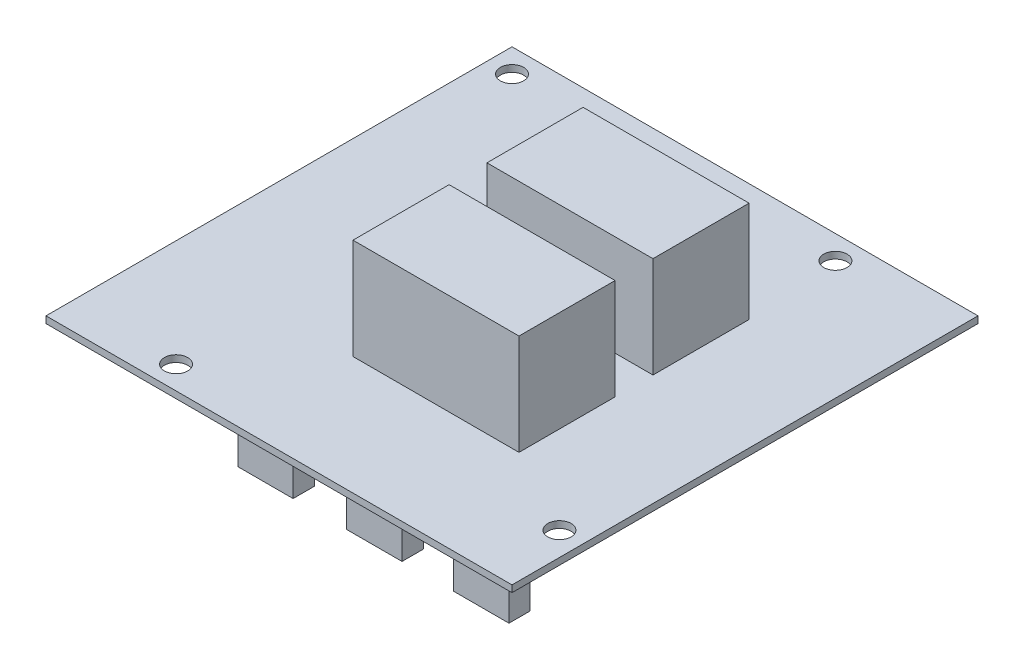
SolidWorks part; units mm, degrees
ref_plane "Front Plane" through (0, 0, 0) normal (0, 0, 1) x (1, 0, 0)
ref_plane "Top Plane" through (0, 0, 0) normal (0, 1, 0) x (1, 0, 0)
ref_plane "Right Plane" through (0, 0, 0) normal (1, 0, 0) x (0, 0, -1)
sketch "Esquisse1" plane through (0, 0, 0) normal (0, 1, 0) x (1, 0, 0)
  line L1 (-40, -40) -> (40, -40)
  line L2 (-40, -40) -> (-40, 40)
  line L3 (-40, 40) -> (40, 40)
  line L4 (40, -40) -> (40, 40)
  circle A0 centre (-35.94, 35.94) radius 2
  circle A1 centre (19.58, 35.94) radius 2
  circle A2 centre (35.94, -27.79) radius 2
  circle A3 centre (-21.64, -36.03) radius 2
  point P0 (0, 0)
  point P6 (0, 40)
  point P7 (40, 0)
  point P16 (0, 0)
  point P18 (29.6759, 35.463)
  dimension "D11" = 4
  dimension "D1" = 80
  dimension "D2" = 80
  dimension "D3" = 4.06
  dimension "D4" = 4.06
  dimension "D5" = 4.06
  dimension "D6" = 20.42
  dimension "D7" = 4.06
  dimension "D8" = 12.21
  dimension "D9" = 3.97
  dimension "D10" = 18.36
extrude "Boss.-Extru.1" add sketch "Esquisse1" along normal blind 1.16
sketch "Esquisse2" plane through (0, 1.16, 0) normal (0, 1, 0) x (1, 0, 0)
  line L0 (40, -40) -> (40, 40) construction
  line L1 (-7.6, 19.8) -> (20.9, 19.8)
  line L2 (-7.6, 19.8) -> (-7.6, 3.3)
  line L3 (-7.6, 3.3) -> (20.9, 3.3)
  line L4 (20.9, 19.8) -> (20.9, 3.3)
  line L5 (-7.6, -3.2) -> (20.9, -3.2)
  line L6 (-7.6, -3.2) -> (-7.6, -19.7)
  line L7 (-7.6, -19.7) -> (20.9, -19.7)
  line L8 (20.9, -3.2) -> (20.9, -19.7)
  line L9 (-40, -40) -> (40, -40) construction
  dimension "D1" = 6.5
  dimension "D2" = 28.5
  dimension "D3" = 19.1
  dimension "D4" = 20.3
  dimension "D5" = 16.5
extrude "Boss.-Extru.2" add sketch "Esquisse2" along normal blind 17.3
sketch "Esquisse3" plane through (0, 0, 0) normal (0, -1, 0) x (1, 0, 0)
  line L0 (-40, 40) -> (40, 40) construction
  line L1 (38.28, 35.15) -> (28.78, 35.15)
  line L2 (38.28, 35.15) -> (38.28, 38.8)
  line L3 (38.28, 38.8) -> (28.78, 38.8)
  line L4 (28.78, 35.15) -> (28.78, 38.8)
  line L5 (19.92, 35.15) -> (10.42, 35.15)
  line L6 (19.92, 35.15) -> (19.92, 38.8)
  line L7 (19.92, 38.8) -> (10.42, 38.8)
  line L8 (10.42, 35.15) -> (10.42, 38.8)
  line L9 (1.22, 35.15) -> (-8.28, 35.15)
  line L10 (1.22, 35.15) -> (1.22, 38.8)
  line L11 (1.22, 38.8) -> (-8.28, 38.8)
  line L12 (-8.28, 35.15) -> (-8.28, 38.8)
  line L13 (40, 40) -> (40, -40) construction
  line L14 (40, -40) -> (-40, -40) construction
  line L15 (5.1, -17.2) -> (1.45, -17.2)
  line L16 (5.1, -17.2) -> (5.1, -7.7)
  line L17 (5.1, -7.7) -> (1.45, -7.7)
  line L18 (1.45, -17.2) -> (1.45, -7.7)
  line L19 (-35.15, -24.5) -> (-38.8, -24.5)
  line L20 (-35.15, -24.5) -> (-35.15, -15)
  line L21 (-35.15, -15) -> (-38.8, -15)
  line L22 (-38.8, -24.5) -> (-38.8, -15)
  line L23 (-10.5, -11.4) -> (-15.5, -11.4)
  line L24 (-10.5, -11.4) -> (-10.5, -5.05)
  line L25 (-10.5, -5.05) -> (-15.5, -5.05)
  line L26 (-15.5, -11.4) -> (-15.5, -5.05)
  line L27 (-40, -40) -> (-40, 40) construction
  dimension "D1" = 9.5
  dimension "D2" = 3.65
  dimension "D3" = 1.2
  dimension "D4" = 1.72
  dimension "D5" = 8.86
  dimension "D6" = 9.2
  dimension "D7" = 22.8
  dimension "D8" = 34.9
  dimension "D9" = 6.35
  dimension "D10" = 5
  dimension "D11" = 28.6
  dimension "D12" = 24.5
  dimension "D13" = 1.2
  dimension "D14" = 15.5
extrude "Boss.-Extru.3" add sketch "Esquisse3" along normal blind 6
